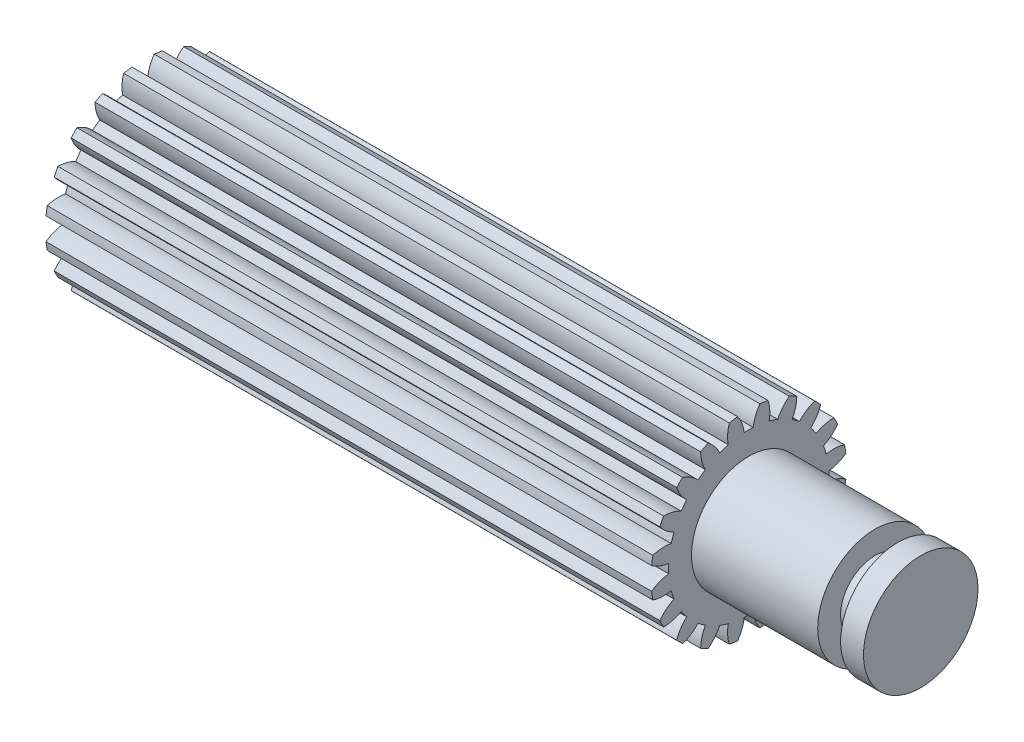
SolidWorks part; units mm, degrees
ref_plane "Plane1" through (0, 0, 0) normal (0, 0, 1) x (1, 0, 0)
ref_plane "Plane2" through (0, 0, 0) normal (0, 1, 0) x (1, 0, 0)
ref_plane "Plane3" through (0, 0, 0) normal (1, 0, 0) x (0, 0, -1)
sketch "HoldingSke" plane through (0, 0, 0) normal (0, 1, 0) x (1, 0, 0)
  line L0 (0, 0) -> (0.4698, -0.171)
  line L1 (-15, 0) -> (100, 0) construction
  line L2 (0, 0) -> (-2.1039, 2.3779)
  line L3 (0, 0) -> (-11.863, 4.5341)
  line L4 (0, 0) -> (8.1152, 2.9537)
  line L5 (0, 0) -> (-46.8476, -17.4728)
  line L6 (0, 0) -> (-9.9476, -6.7116)
  line L7 (-2.1039, 2.3779) -> (8.6586, 51.2059)
  line L8 (-76.2, 54.61) -> (-76.1, 54.61)
  line L9 (-71.009, 38.7566) -> (-53.1078, 45.2721)
  line L10 (-76.2, 71.12) -> (104.1128, 71.12)
  line L11 (0, 0) -> (-12, 0)
  line L12 (-76.2, 101.6) -> (-76.133, 101.6)
  line L13 (24.9733, 27.94) -> (52.9518, 28.4284)
  line L14 (24.9733, 27.94) -> (24.9743, 27.94)
  line L15 (24.9733, 27.94) -> (100.4006, 29.5858)
  line L16 (-63.627, -2) -> (-12.827, -2)
  circle A0 centre (0, 0) radius 0.4
  circle A1 centre (0, 0) radius 17.499
  circle A2 centre (0, 0) radius 37.5
  circle A3 centre (0, 0) radius 0.4
  dimension "MHD" = 34.998
  dimension "Hub_dia" = 75
  dimension "Bore" = 0.8
  dimension "MBD" = 0.8
  dimension "Num_teeth" = 20
  dimension "Pitch" = 0.5
  dimension "Overall_len" = 50
  dimension "Show_teeth" = 20
  dimension "Thickness" = 12
  dimension "OAL" = 50.0001
  dimension "T_dim" = 0.1
  dimension "Ap" = 20
  dimension "H" = 19.05
  dimension "Pitch_radius" = 180.3128
  dimension "Width" = 12
  dimension "Backlash" = 0.067
  dimension "Addendum_fac" = 1
  dimension "Dedendum_fac" = 1.25
  dimension "Clearance_fac" = 0.25
  dimension "Dedendum_add" = 0.001
  dimension "Module" = 2
sketch "BasProSke" plane through (0, 0, 0) normal (0, 1, 0) x (1, 0, 0)
  line L0 (-10, 0) -> (60, 0) construction
  line L1 (0, 0) -> (0, 22)
  line L2 (0, 0) -> (132.2299, 0)
  line L3 (132.2299, 0) -> (132.2299, 22)
  line L4 (132.2299, 22) -> (0, 22)
  dimension "Thickness" = 132.2299
  dimension "Diameter" = 44
revolve "Base-Revolve" add sketch "BasProSke" angle 360 about L0
sketch "TooCutSke" plane through (0, 0, 0) normal (1, 0, 0) x (0, 0, -1)
  line L1 (0, 0) -> (0, 107) construction
  line L2 (0, 0) -> (-1.6864, 19.9288) construction
  line L3 (0, 0) -> (-6.2409, 39.4033) construction
  line L4 (-1.6864, 19.9288) -> (-3.1204, 19.7016) construction
  arc A0 (0.9862, 17.4712) -> (-0.9862, 17.4712) centre (0, 0) ccw
  arc A1 (2.9329, 21.8293) -> (-2.9329, 21.8293) centre (0, 0) ccw
  circle A2 centre (0, 0) radius 20 construction
  circle A3 centre (0, 0) radius 18.7939 construction
  arc A4 (-0.9862, 17.4712) -> (-2.9329, 21.8293) centre (-8.9313, 16.536) ccw
  arc A5 (2.9329, 21.8293) -> (0.9862, 17.4712) centre (8.9313, 16.536) ccw
  dimension "Root_dia" = 34.998
  dimension "Overcut_dia" = 44.0508
  dimension "Pitch_dia" = 40
  dimension "Base_dia" = 37.5877
  dimension "Flank_rad" = 8
  dimension "Half_ang" = 9
  dimension "Half_CT" = 1.4519
extrude "ToothCut" cut sketch "TooCutSke" along normal through all
fillet "Breaks" [suppressed] radius 0.04
fillet "RootFillets" [suppressed] radius 0.501
pattern_circular "TeethCuts" count 20 every 18 about axis through (-10, 0, 0) along (1, 0, 0) of "ToothCut", "RootFillets", "Breaks"
sketch "HubNeaOneSke" plane through (0, 0, 0) normal (-1, 0, 0) x (0, 0, 1)
  circle A0 centre (0, 0) radius 17.499
  dimension "Diameter" = 34.998
extrude "HubNearOne" [suppressed] add sketch "HubNeaOneSke" along normal blind 38.0001
sketch "HubNeaBotSke" plane through (0, 0, 0) normal (-1, 0, 0) x (0, 0, 1)
  circle A0 centre (0, 0) radius 17.499
  dimension "Diameter" = 34.998
extrude "HubNearBoth" [suppressed] add sketch "HubNeaBotSke" along normal blind 19
ref_plane "FarPln" through (132.2299, 0, 0) normal (1, 0, 0) x (0, 0, -1)
sketch "HubFarSke" plane through (132.2299, 0, 0) normal (1, 0, 0) x (0, 0, -1)
  circle A0 centre (0, 0) radius 17.499
  dimension "Diameter" = 34.998
extrude "HubFar" [suppressed] add sketch "HubFarSke" along normal blind 19
sketch "BorSke" plane through (0, 0, 0) normal (1, 0, 0) x (0, 0, -1)
  circle A0 centre (0, 0) radius 0.4
  dimension "Diameter" = 0.8
extrude "Bore" cut sketch "BorSke" along normal mid plane 100.0001
sketch "KeySke" plane through (0, 0, 0) normal (1, 0, 0) x (0, 0, -1)
  line L0 (-0.05, 0) -> (-0.05, 0.5)
  line L1 (-0.05, 0.5) -> (0.05, 0.5)
  line L2 (0.05, 0.5) -> (0.05, 0)
  line L3 (0, 0) -> (0, 34) construction
  line L4 (-0.05, 0) -> (0.05, 0)
  dimension "Offset" = 0.5
  dimension "Width" = 0.1
extrude "Keyway" [suppressed] cut sketch "KeySke" along normal mid plane 100.0001
pattern_circular "Keyway2" [suppressed] count 2 every 90 about axis through (-10, 0, 0) along (1, 0, 0)
sketch "Sketch1" plane through (132.2299, 0, 0) normal (1, 0, 0) x (0, 0, -1)
  circle A0 centre (0, 0) radius 21.3427
  circle A1 centre (0, 0) radius 22
extrude "Cut-Extrude1" cut sketch "Sketch1" against normal through all
scale "Scale1" scale about origin uniform scaling yes scale factor 0.4
sketch "Sketch6" plane through (52.892, 0, 0) normal (1, 0, 0) x (0, 0, -1)
  circle A0 centre (0, 0) radius 5
extrude "Boss-Extrude3" add sketch "Sketch6" along normal blind 15.0234
sketch "Sketch7" plane through (0, 0, 0) normal (-1, 0, 0) x (0, 0, 1)
  line L1 (2.5, 0) -> (2.5, 4.3301)
  line L2 (2.5, 0) -> (2.5, -4.3301)
  arc A1 (2.5, 4.3301) -> (2.5, -4.3301) centre (0, 0) ccw
extrude "Cut-Extrude2" cut sketch "Sketch7" against normal blind 10
ref_plane "Plane4" through (65.9154, 0, 0) normal (1, 0, 0) x (0, 0, -1)
sketch "Sketch8" plane through (65.9154, 0, 0) normal (1, 0, 0) x (0, 0, -1)
  circle A0 centre (0, 0) radius 3
  circle A1 centre (0, 0) radius 5
  circle A2 centre (0, 0) radius 5 construction
  dimension "D1" = 2
extrude "Cut-Extrude3" cut sketch "Sketch8" against normal blind 2
equation "' \"Module@HoldingSke\" = 6.35"
equation "' \"Num_teeth@HoldingSke\" = 12"
equation "' \"Ap@HoldingSke\" =  20"
equation "' \"Ap@HoldingSke\" = 20"
equation "' \"Width@HoldingSke\" = 0.5 * 25.4"
equation "' \"Hub_dia@HoldingSke\"= 1 * 25.4"
equation "' \"Hub_dia@HoldingSke\" = 1 * 25.4"
equation "' \"Overall_len@HoldingSke\" = 1.0 * 25.4"
equation "' \"Bore@HoldingSke\" = 0.75 * 25.4"
equation "' \"T_dim@HoldingSke\" = 0.1 * 25.4"
equation "' \"Width@KeySke\" = 0.25 * 25.4"
equation "' \"Show_teeth@HoldingSke\" = 13"
equation "' \"Backlash@HoldingSke\" = 0.009 * 25.4"
equation "' \"Addendum_fac@HoldingSke\" = 1.0"
equation "' \"Dedendum_fac@HoldingSke\" = 1.25"
equation "' \"Dedendum_add@HoldingSke\" = 0.00005 * 25.4"
equation "' \"Clearance_fac@HoldingSke\" = 0.25"
equation "\"Pitch@HoldingSke\" = 1 / \"Module@HoldingSke\""
equation "\"Overcut_dia@TooCutSke\" = (\"Num_teeth@HoldingSke\" + 2 * \"Addendum_fac@HoldingSke\") / \"Pitch@HoldingSke\" + 0.002 * 25.4"
equation "\"Pitch_dia@TooCutSke\" = \"Num_teeth@HoldingSke\" / \"Pitch@HoldingSke\""
equation "\"Base_dia@TooCutSke\" = \"Num_teeth@HoldingSke\" / \"Pitch@HoldingSke\" * cos((\"Ap@HoldingSke\"  * 3.14159265 / 180))"
equation "\"Root_dia@TooCutSke\" = (\"Num_teeth@HoldingSke\" + 2) / \"Pitch@HoldingSke\" - 2 * (\"Addendum_fac@HoldingSke\" + \"Dedendum_fac@HoldingSke\") / \"Pitch@HoldingSke\" - \"Dedendum_add@HoldingSke\" * 2"
equation "\"Half_ang@TooCutSke\" = 180 / \"Num_teeth@HoldingSke\""
equation "\"Half_CT@TooCutSke\" = \"Num_teeth@HoldingSke\" / \"Pitch@HoldingSke\" * sin((3.14159265 / 2 / \"Num_teeth@HoldingSke\")) / 2 - 7 * \"Backlash@HoldingSke\" / 4"
equation "\"Flank_rad@TooCutSke\" = \"Num_teeth@HoldingSke\" / \"Pitch@HoldingSke\" / 5"
equation "\"Radius@RootFillets\" = \"Clearance_fac@HoldingSke\" / \"Pitch@HoldingSke\" + \"Dedendum_add@HoldingSke\""
equation "\"Break_rad@Breaks\" = 0.02 / \"Pitch@HoldingSke\""
equation "\"Thickness@HoldingSke\" = \"Width@HoldingSke\""
equation "\"OAL@HoldingSke\" = \"Thickness@HoldingSke\""
equation "\"MHD@HoldingSke\" = (\"Num_teeth@HoldingSke\" + 2) / \"Pitch@HoldingSke\" - 2 * (\"Addendum_fac@HoldingSke\" + \"Dedendum_fac@HoldingSke\")  / \"Pitch@HoldingSke\" - \"Dedendum_add@HoldingSke\" * 2"
equation "\"MBD@HoldingSke\" = (\"Num_teeth@HoldingSke\" + 2) / \"Pitch@HoldingSke\" - 2 * (\"Addendum_fac@HoldingSke\" + \"Dedendum_fac@HoldingSke\")  / \"Pitch@HoldingSke\" - \"Dedendum_add@HoldingSke\" * 2 - 0.002 * 25.4"
equation "\"MHD@HoldingSke\" = ((sgn( \"MHD@HoldingSke\" - \"Hub_dia@HoldingSke\" )-1)*( \"MHD@HoldingSke\" - \"Hub_dia@HoldingSke\" ))/-2+ \"Hub_dia@HoldingSke\""
equation "\"MBD@HoldingSke\" = ((sgn( \"MBD@HoldingSke\" - \"Bore@HoldingSke\" )-1)*( \"MBD@HoldingSke\" - \"Bore@HoldingSke\" ))/-2+ \"Bore@HoldingSke\""
equation "\"OAL@HoldingSke\" = ((sgn( \"OAL@HoldingSke\" - \"Overall_len@HoldingSke\" )+1)*( \"OAL@HoldingSke\" - \"Overall_len@HoldingSke\" ))/2 + \"Overall_len@HoldingSke\" + 0.000002 * 25.4"
equation "\"Num_teeth@TeethCuts\" = int( \"Show_teeth@HoldingSke\" ) + 1"
equation "\"Num_teeth@TeethCuts\" = ((sgn( \"Num_teeth@TeethCuts\" - \"Num_teeth@HoldingSke\" )-1)*( \"Num_teeth@TeethCuts\" - \"Num_teeth@HoldingSke\" ))/-2+ \"Num_teeth@HoldingSke\""
equation "\"Num_teeth@TeethCuts\" = ((sgn( \"Num_teeth@TeethCuts\" - 2.0)+1)*( \"Num_teeth@TeethCuts\" - 2.0))/2 +2.0"
equation "\"Angle@TeethCuts\" = 360.0 / \"Num_teeth@HoldingSke\""
equation "\"Diameter@BasProSke\" = (\"Num_teeth@HoldingSke\" + 2 * \"Addendum_fac@HoldingSke\") / \"Pitch@HoldingSke\""
equation "' \"Fillet_rad@BasProSke\" =  \"Thickness@HoldingSke\" * 0.05"
equation "' \"Fillet_rad@BasProSke\" = \"Thickness@HoldingSke\" * 0.05"
equation "\"MHD@HoldingSke\" = ((sgn( \"MHD@HoldingSke\" - \"Root_dia@TooCutSke\" )-1)*( \"MHD@HoldingSke\" - \"Root_dia@TooCutSke\" ))/-2+ \"Root_dia@TooCutSke\""
equation "\"Diameter@HubNeaOneSke\" = \"MHD@HoldingSke\""
equation "\"Length@HubNearOne\" = \"OAL@HoldingSke\" - \"Thickness@BasProSke\""
equation "\"Diameter@HubNeaBotSke\" = \"MHD@HoldingSke\""
equation "\"Length@HubNearBoth\" = ( \"OAL@HoldingSke\" - \"Thickness@BasProSke\" ) / 2.0"
equation "\"Thickness@FarPln\" = \"Thickness@BasProSke\""
equation "\"Diameter@HubFarSke\" = \"MHD@HoldingSke\""
equation "\"Length@HubFar\" = ( \"OAL@HoldingSke\" - \"Thickness@BasProSke\" ) / 2.0"
equation "\"Diameter@BorSke\" = \"MBD@HoldingSke\""
equation "\"D1@Bore\" = \"OAL@HoldingSke\" * 2.0"
equation "\"D1@Keyway\" = \"OAL@HoldingSke\" * 2.0"
equation "\"Offset@KeySke\" = \"T_dim@HoldingSke\" + \"MBD@HoldingSke\" / 2.0"
